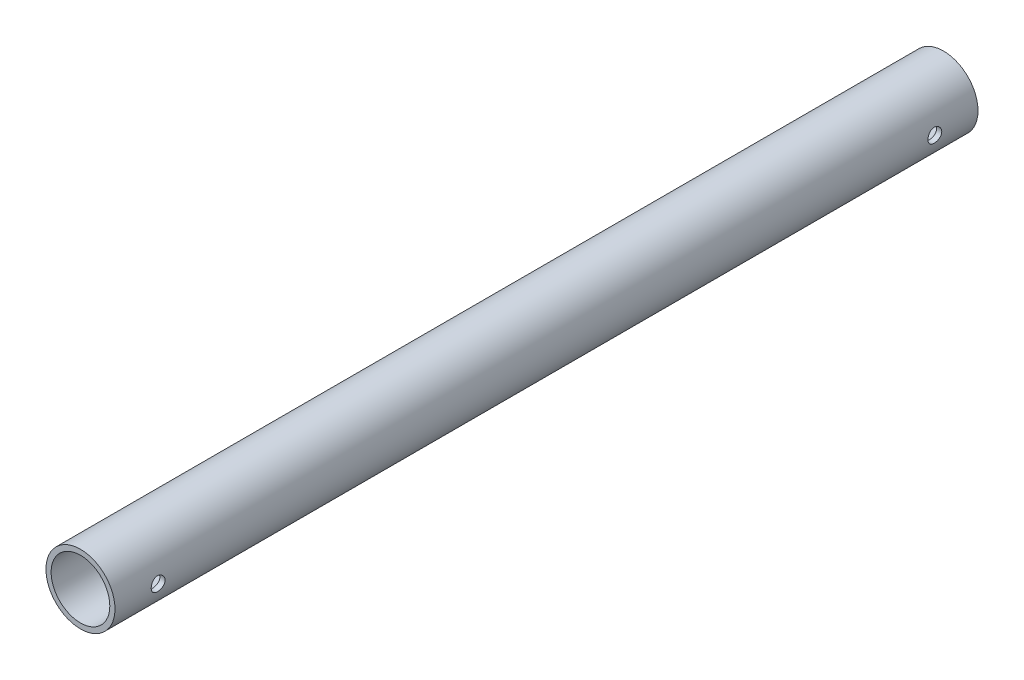
SolidWorks part; units mm, degrees
ref_plane "Front Plane" through (0, 0, 0) normal (0, 0, 1) x (1, 0, 0)
ref_plane "Top Plane" through (0, 0, 0) normal (0, 1, 0) x (1, 0, 0)
ref_plane "Right Plane" through (0, 0, 0) normal (1, 0, 0) x (0, 0, -1)
sketch "Sketch1" plane through (0, 0, 0) normal (0, 0, 1) x (1, 0, 0)
  circle A0 centre (0, 0) radius 8.5
  circle A1 centre (0, 0) radius 10
  dimension "D1" = 20
  dimension "D2" = 1.5
extrude "Boss-Extrude1" add sketch "Sketch1" along normal blind 125
sketch "Sketch2" plane through (0, 0, 0) normal (1, 0, 0) x (0, 0, -1)
  line L0 (-125, 10) -> (-125, -10) construction
  line L1 (-170, 30.5417) -> (-170, -40.4629) construction
  circle A0 centre (-112.5, 0) radius 2
  circle A1 centre (-227.5, 0) radius 2
  dimension "D1" = 4
  dimension "D2" = 12.5
extrude "Cut-Extrude1" cut sketch "Sketch2" against normal through all both and the other way through all
mirror "Mirror1" about plane through (0, 0, 0) normal (0, 0, 1) of "Boss-Extrude1", "Cut-Extrude1"
